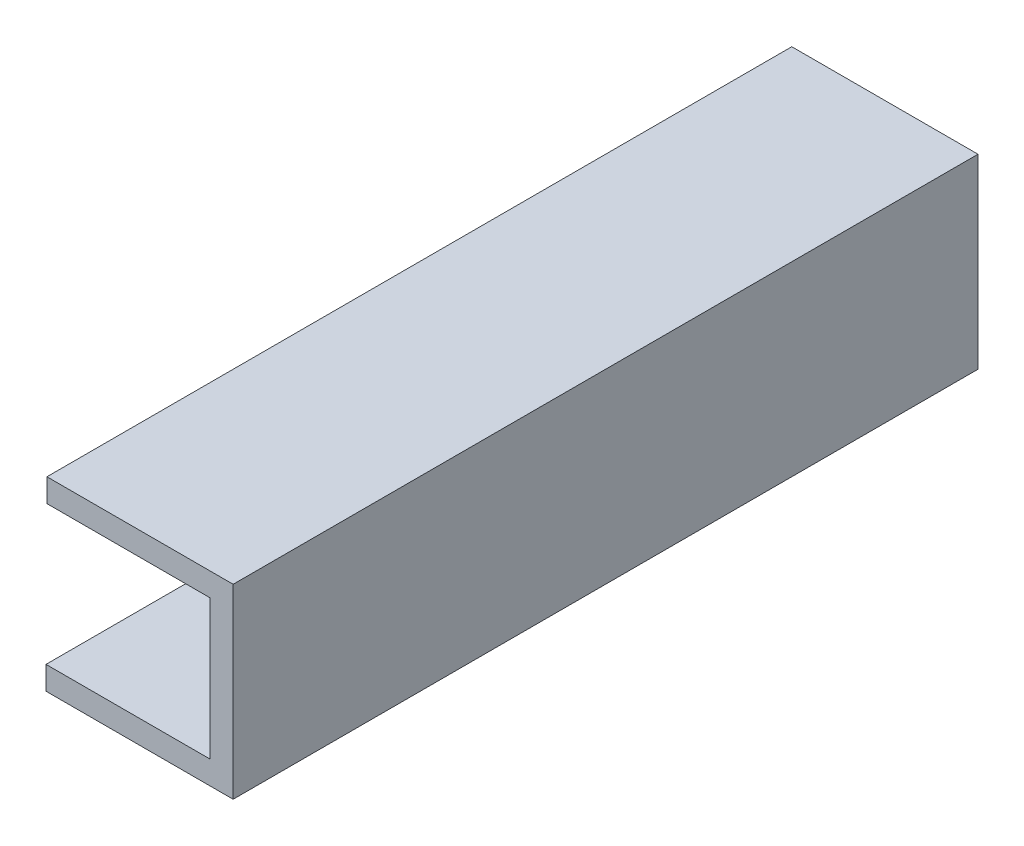
SolidWorks part; units mm, degrees
ref_plane "Front Plane" through (0, 0, 0) normal (0, 0, 1) x (1, 0, 0)
ref_plane "Top Plane" through (0, 0, 0) normal (0, 1, 0) x (1, 0, 0)
ref_plane "Right Plane" through (0, 0, 0) normal (1, 0, 0) x (0, 0, -1)
sketch "Sketch1" plane through (0, 0, 0) normal (0, 0, 1) x (1, 0, 0)
  line L0 (-35.9316, 6.8404) -> (-35.9316, 3.6654)
  line L1 (-35.9316, 3.6654) -> (-13.7066, 3.6654)
  line L2 (-13.7066, 3.6654) -> (-13.7066, -15.3846)
  line L3 (-13.7066, -15.3846) -> (-36.0586, -15.3846)
  line L4 (-36.0586, -15.3846) -> (-36.0586, -18.5596)
  line L5 (-36.0586, -18.5596) -> (-10.5316, -18.5596)
  line L6 (-10.5316, -18.5596) -> (-10.5316, 6.8404)
  line L7 (-10.5316, 6.8404) -> (-35.9316, 6.8404)
  dimension "D1" = 22.225
  dimension "D2" = 22.352
  dimension "D3" = 19.05
  dimension "D4" = 3.175
  dimension "D5" = 3.175
  dimension "D6" = 25.4
  dimension "D7" = 25.4
extrude "Boss-Extrude2" add sketch "Sketch1" along normal blind 101.6
